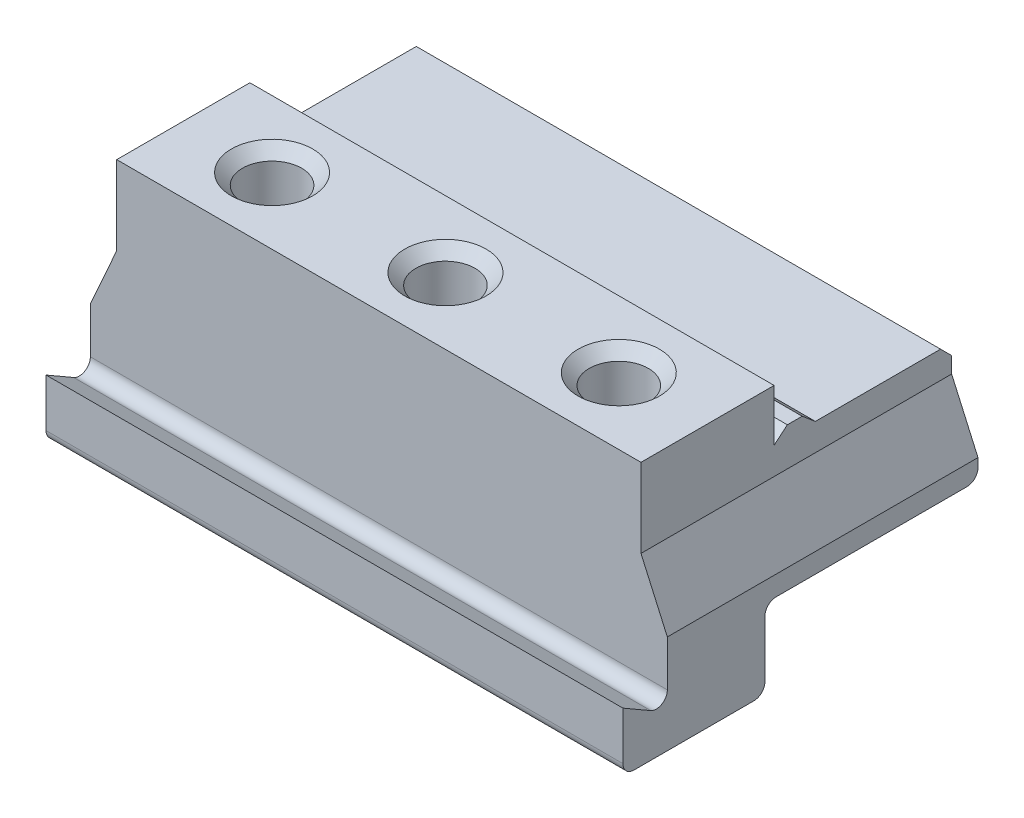
SolidWorks part; units mm, degrees
material "Cast Carbon Steel"
ref_plane "Front Plane" through (0, 0, 0) normal (0, 0, 1) x (1, 0, 0)
ref_plane "Top Plane" through (0, 0, 0) normal (0, 1, 0) x (1, 0, 0)
ref_plane "Right Plane" through (0, 0, 0) normal (1, 0, 0) x (0, 0, -1)
sketch "Sketch1" plane through (0, 0, 0) normal (1, 0, 0) x (0, 0, -1)
  line L0 (-1.5, 0) -> (-1.5, -7.67)
  line L1 (-3, -9.17) -> (-19.2, -9.17)
  line L2 (-20.7, -7.67) -> (-20.7, -1.17)
  line L3 (-20.7, -1.17) -> (-16.95, -3.3351)
  line L4 (-14.7, -2.036) -> (-14.7, 22.83)
  line L5 (-14.7, 22.83) -> (3.3, 22.83)
  line L6 (3.3, 22.83) -> (3.3, 15.83)
  line L7 (3.3, 15.83) -> (5.0876, 17.33)
  line L8 (5.0876, 17.33) -> (7.0876, 17.33)
  line L9 (7.0876, 17.33) -> (8.8753, 15.83)
  line L10 (8.8753, 15.83) -> (25.8, 15.83)
  line L12 (27.3, 14.33) -> (27.3, 3)
  line L13 (25.8, 1.5) -> (0, 1.5)
  line L15 (25.8, 15.83) -> (27.3, 14.33)
  arc A0 (0, 1.5) -> (-1.5, 0) centre (0, 0) ccw
  arc A1 (-1.5, -7.67) -> (-3, -9.17) centre (-3, -7.67) cw
  arc A2 (-19.2, -9.17) -> (-20.7, -7.67) centre (-19.2, -7.67) cw
  arc A3 (-16.95, -3.3351) -> (-14.7, -2.036) centre (-16.2, -2.036) ccw
  arc A4 (27.3, 3) -> (25.8, 1.5) centre (25.8, 3) cw
  point P21 (0, 0)
  point P22 (27.3, 15.83)
  point P25 (27.3, 4.2494)
  point P26 (0, 0)
  point P27 (-1.5, -3.835)
  point P28 (27.3, 4.1842)
  point P29 (27.3, 3.7455)
  point P30 (27.3, 4.1842)
  point P31 (27.3, 3.7654)
  point P32 (27.3, 3.6888)
  point P33 (8.6966, 3.3356)
  point P34 (9.1538, 3.3356)
  point P35 (0, 0)
  point P36 (0, 1.1655)
  point P37 (27.3, 9.3729)
  point P38 (-15.8253, -2.6849)
  dimension "D1" = 1.5
  dimension "D2" = 6
  dimension "D3" = 48
  dimension "D4" = 28.8
  dimension "D5" = 60
  dimension "D6" = 8
  dimension "D7" = 18
  dimension "D8" = 40
  dimension "D9" = 2
  dimension "D10" = 1.5
  dimension "D11" = 100
  dimension "D12" = 7
  dimension "D13" = 32
  dimension "D14" = 10.67
extrude "Boss-Extrude1" add sketch "Sketch1" along normal mid plane 78
sketch "Sketch2" plane through (0, 0, 0) normal (0, 0, 1) x (1, 0, 0)
  line L0 (-39, 22.83) -> (-35.4382, 22.83)
  line L1 (39, 22.83) -> (-39, 22.83) construction
  line L2 (-35.4382, 22.83) -> (-35.4382, 12.1633)
  line L3 (-35.4382, 12.1633) -> (-39, 4.1633)
  line L4 (-39, 22.83) -> (-39, -2.036) construction
  line L5 (-39, 4.1633) -> (-39, 22.83)
  dimension "D1" = 8
  dimension "D2" = 10.6667
  dimension "D3" = 24
extrude "Cut-Extrude1" cut sketch "Sketch2" against normal through all both and the other way through all
mirror "Mirror2" about plane through (0, 0, 0) normal (1, 0, 0) of "Cut-Extrude1"
sketch "Sketch3" plane through (0, 22.83, 0) normal (0, 1, 0) x (1, 0, 0)
  line L0 (-35.4382, -5.7) -> (35.4382, -5.7) construction
  line L1 (-35.4382, 3.3) -> (-35.4382, -14.7) construction
  line L2 (35.4382, 3.3) -> (35.4382, -14.7) construction
  circle A0 centre (23.4382, -5.7) radius 4
  circle A1 centre (0, -5.7) radius 4
  circle A2 centre (-23.4382, -5.7) radius 4
  dimension "D3" = 8
  dimension "D1" = 12
  dimension "D2" = 12
extrude "Cut-Extrude2" cut sketch "Sketch3" against normal blind 10 and the other way through all
chamfer "Chamfer1" distance 1.5 angle 45 3 edges at (-23.4382, 22.83, 1.7) (0, 22.83, 1.7) (23.4382, 22.83, 1.7)
equation "\"A\"= 78"
equation "\"B\"= 32"
equation "\"C\"= 48"
equation "\"D3@Sketch1\"=\"C\""
equation "\"D13@Sketch1\"=\"B\""
equation "\"D1@Boss-Extrude1\"=\"A\""
equation "\"D2@Sketch2\"=\"B\"/3"
